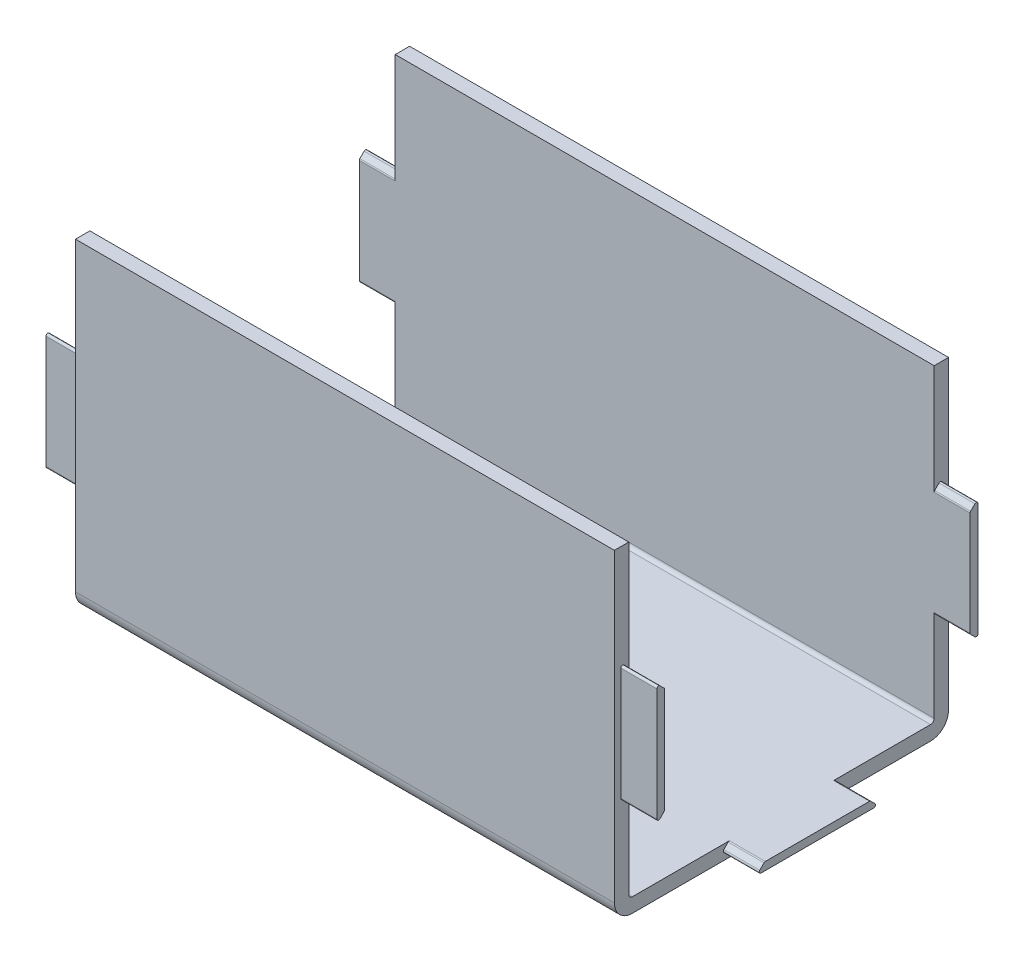
SolidWorks part; units mm, degrees
ref_plane "前基準面" through (0, 0, 0) normal (0, 0, 1) x (1, 0, 0)
ref_plane "上基準面" through (0, 0, 0) normal (0, 1, 0) x (1, 0, 0)
ref_plane "右基準面" through (0, 0, 0) normal (1, 0, 0) x (0, 0, -1)
sketch "草圖1" plane through (0, 0, 0) normal (0, 1, 0) x (1, 0, 0)
  line L1 (-75, -46.5) -> (75, -46.5)
  line L2 (-75, -46.5) -> (-75, 46.5)
  line L3 (-75, 46.5) -> (75, 46.5)
  line L4 (75, -46.5) -> (75, 46.5)
  line L5 (-75, -46.5) -> (75, 46.5) construction
  line L6 (-75, 46.5) -> (75, -46.5) construction
  point P0 (0, 0)
  dimension "D1" = 150
  dimension "D2" = 93
extrude "填料-伸長1" add sketch "草圖1" along normal blind 90
fillet "圓角1" radius 5 2 edges at (0, 0, -46.5) (0, 0, 46.5)
shell "薄殼1" thickness 4
sketch "草圖2" plane through (75, 0, 0) normal (1, 0, 0) x (0, 0, -1)
  line L0 (-42.5, 59.7) -> (42.5, 59.7) construction
  line L1 (0, 55) -> (0, -55) construction
  line L2 (42.5, 90) -> (42.5, 5) construction
  line L3 (42.5, 59.7) -> (44.7, 61.9)
  line L4 (44.7, 61.9) -> (44.7, 28.1)
  line L5 (44.7, 28.1) -> (42.5, 30.3)
  line L6 (42.5, 30.3) -> (14.7, 30.3) construction
  line L7 (14.7, 30.3) -> (14.7, 4) construction
  line L8 (-41.5, 4) -> (41.5, 4) construction
  line L9 (14.7, 4) -> (16.9, 1.8)
  line L10 (16.9, 1.8) -> (-16.9, 1.8)
  line L11 (42.5, 90) -> (46.5, 90) construction
  line L12 (42.5, 59.7) -> (42.5, 30.3)
  line L13 (14.7, 4) -> (-14.7, 4)
  line L14 (-14.7, 30.3) -> (-14.7, 4) construction
  line L15 (-42.5, 30.3) -> (-14.7, 30.3) construction
  line L16 (-42.5, 59.7) -> (-42.5, 30.3)
  line L17 (-14.7, 4) -> (-16.9, 1.8)
  line L18 (-44.7, 28.1) -> (-42.5, 30.3)
  line L19 (-44.7, 61.9) -> (-44.7, 28.1)
  line L20 (-42.5, 59.7) -> (-44.7, 61.9)
  point P0 (0, 4)
  point P22 (0, 59.7)
  point P23 (0, 1.8)
  dimension "D1" = 2.2
  dimension "D2" = 135
  dimension "D3" = 135
  dimension "D4" = 30.3
  dimension "D5" = 29.4
  dimension "D6" = 14.7
  dimension "D7" = 2.2
extrude "填料-伸長3" add sketch "草圖2" along normal blind 10
fillet "圓角2" radius 0.5 12 edges at (80, 1.8, 16.9) (80, 4, 14.7) (80, 1.8, -16.9) (80, 4, -14.7) (80, 28.1, 44.7) (80, 30.3, 42.5) (80, 59.7, 42.5) (80, 61.9, 44.7) (80, 30.3, -42.5) (80, 28.1, -44.7) (80, 59.7, -42.5) (80, 61.9, -44.7)
mirror "鏡射1" about plane through (0, 0, 0) normal (1, 0, 0) of "填料-伸長3", "圓角2"
